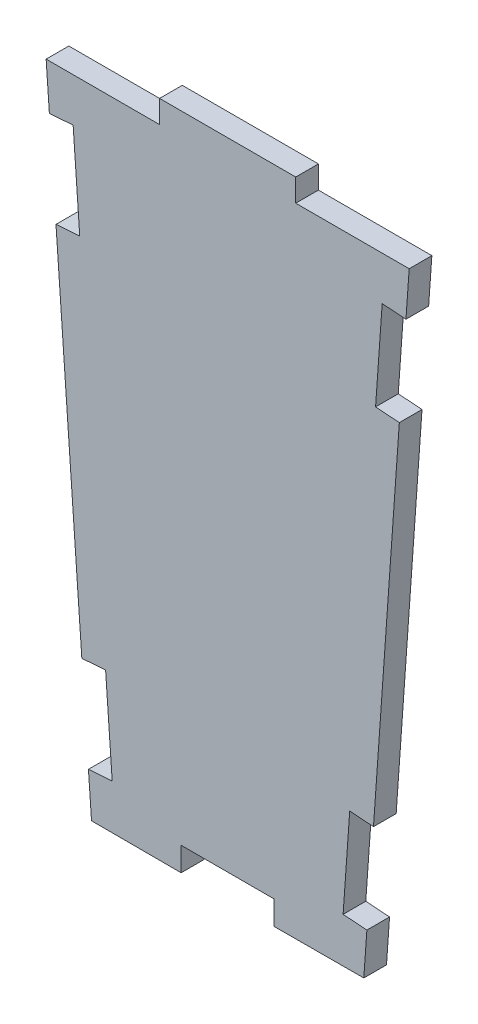
SolidWorks part; units mm, degrees
ref_plane "Front Plane" through (0, 0, 0) normal (0, 0, 1) x (1, 0, 0)
ref_plane "Top Plane" through (0, 0, 0) normal (0, 1, 0) x (1, 0, 0)
ref_plane "Right Plane" through (0, 0, 0) normal (1, 0, 0) x (0, 0, -1)
sketch "Model" plane through (0, 0, 0) normal (0, 0, 1) x (1, 0, 0)
  line L0 (354.4597, -23.3264) -> (359.6964, -22.9533)
  line L1 (383.497, -148.4797) -> (403.9964, -148.4797)
  line L2 (425.8801, -123.7434) -> (420.6434, -123.3703)
  line L3 (353.747, -13.3232) -> (354.4597, -23.3264)
  line L4 (383.4969, -153.7291) -> (383.497, -148.4797)
  line L5 (420.6434, -123.3703) -> (419.1865, -143.8185)
  line L6 (366.8507, -123.3703) -> (368.3075, -143.8185)
  line L7 (426.3408, -43.4015) -> (431.5775, -43.7746)
  line L8 (378.747, -8.3232) -> (408.747, -8.3232)
  line L9 (363.0708, -144.1916) -> (363.747, -153.6832)
  line L10 (419.1865, -143.8185) -> (424.4233, -144.1916)
  line L11 (408.747, -8.3232) -> (408.747, -13.3232)
  line L12 (423.747, -153.6832) -> (403.9971, -153.7291)
  line L13 (403.9964, -148.4797) -> (403.9971, -153.7291)
  line L14 (378.747, -8.3232) -> (378.747, -13.3232)
  line L15 (361.6139, -123.7434) -> (366.8507, -123.3703)
  line L16 (433.747, -13.3232) -> (433.0343, -23.3264)
  line L17 (361.1533, -43.4015) -> (355.9165, -43.7746)
  line L18 (431.5775, -43.7746) -> (425.8801, -123.7434)
  line L19 (359.6964, -22.9533) -> (361.1533, -43.4015)
  line L20 (427.7976, -22.9533) -> (426.3408, -43.4015)
  line L21 (355.9165, -43.7746) -> (361.6139, -123.7434)
  line L22 (408.747, -13.3232) -> (433.747, -13.3232)
  line L23 (368.3075, -143.8185) -> (363.0708, -144.1916)
  line L24 (378.747, -13.3232) -> (353.747, -13.3232)
  line L25 (433.0343, -23.3264) -> (427.7976, -22.9533)
  line L26 (363.747, -153.6832) -> (383.4969, -153.7291)
  line L27 (424.4233, -144.1916) -> (423.747, -153.6832)
  line L28 (393.747, -16.3232) -> (393.747, -11.3232)
  line L29 (394.747, -13.3232) -> (393.747, -11.3232)
  line L30 (392.747, -13.3232) -> (393.747, -11.3232)
  line L31 (395.617, -18.1099) -> (395.617, -17.804)
  line L32 (395.617, -17.804) -> (395.6373, -17.7076)
  line L33 (395.6373, -17.7076) -> (395.6982, -17.6183)
  line L34 (395.6982, -17.6183) -> (395.9417, -17.4606)
  line L35 (395.9417, -17.4606) -> (396.2976, -17.3576)
  line L36 (396.2976, -17.3576) -> (396.7409, -17.3232)
  line L37 (396.7409, -17.3232) -> (397.1858, -17.3576)
  line L38 (397.1858, -17.3576) -> (397.5464, -17.4606)
  line L39 (397.5464, -17.4606) -> (397.7852, -17.6151)
  line L40 (397.7852, -17.6151) -> (397.8449, -17.7053)
  line L41 (397.8449, -17.7053) -> (397.8648, -17.804)
  line L42 (397.8648, -17.804) -> (397.8648, -21.1504)
  line L43 (397.8648, -21.1504) -> (397.8449, -21.2464)
  line L44 (397.8449, -21.2464) -> (397.7852, -21.3346)
  line L45 (397.7852, -21.3346) -> (397.5464, -21.4876)
  line L46 (397.5464, -21.4876) -> (397.1796, -21.5953)
  line L47 (397.1796, -21.5953) -> (396.7409, -21.6312)
  line L48 (396.7409, -21.6312) -> (396.307, -21.5953)
  line L49 (396.307, -21.5953) -> (395.9417, -21.4876)
  line L50 (395.9417, -21.4876) -> (395.6982, -21.3315)
  line L51 (395.6982, -21.3315) -> (395.6373, -21.2441)
  line L52 (395.6373, -21.2441) -> (395.617, -21.1504)
  line L53 (395.617, -21.1504) -> (395.617, -20.8445)
  line L54 (395.617, -20.8445) -> (395.617, -21.1504)
  line L55 (395.617, -21.1504) -> (395.6373, -21.2441)
  line L56 (395.6373, -21.2441) -> (395.6982, -21.3315)
  line L57 (395.6982, -21.3315) -> (395.9417, -21.4876)
  line L58 (395.9417, -21.4876) -> (396.307, -21.5953)
  line L59 (396.307, -21.5953) -> (396.7409, -21.6312)
  line L60 (396.7409, -21.6312) -> (397.1796, -21.5953)
  line L61 (397.1796, -21.5953) -> (397.5464, -21.4876)
  line L62 (397.5464, -21.4876) -> (397.7852, -21.3346)
  line L63 (397.7852, -21.3346) -> (397.8449, -21.2464)
  line L64 (397.8449, -21.2464) -> (397.8648, -21.1504)
  line L65 (397.8648, -21.1504) -> (397.8648, -17.804)
  line L66 (397.8648, -17.804) -> (397.8449, -17.7053)
  line L67 (397.8449, -17.7053) -> (397.7852, -17.6151)
  line L68 (397.7852, -17.6151) -> (397.5464, -17.4606)
  line L69 (397.5464, -17.4606) -> (397.1858, -17.3576)
  line L70 (397.1858, -17.3576) -> (396.7409, -17.3232)
  line L71 (396.7409, -17.3232) -> (396.2976, -17.3576)
  line L72 (396.2976, -17.3576) -> (395.9417, -17.4606)
  line L73 (395.9417, -17.4606) -> (395.6982, -17.6183)
  line L74 (395.6982, -17.6183) -> (395.6373, -17.7076)
  line L75 (395.6373, -17.7076) -> (395.617, -17.804)
  line L76 (395.617, -17.804) -> (395.617, -18.1099)
  line L77 (394.874, -17.3232) -> (394.874, -21.6312)
  line L78 (394.874, -21.6312) -> (393.8562, -21.6312)
  line L79 (393.8562, -21.6312) -> (393.4223, -21.5953)
  line L80 (393.4223, -21.5953) -> (393.057, -21.4876)
  line L81 (393.057, -21.4876) -> (392.8135, -21.3315)
  line L82 (392.8135, -21.3315) -> (392.7526, -21.2441)
  line L83 (392.7526, -21.2441) -> (392.7323, -21.1504)
  line L84 (392.7323, -21.1504) -> (392.7323, -17.804)
  line L85 (392.7323, -17.804) -> (392.7526, -17.7076)
  line L86 (392.7526, -17.7076) -> (392.8135, -17.6183)
  line L87 (392.8135, -17.6183) -> (393.057, -17.4606)
  line L88 (393.057, -17.4606) -> (393.4129, -17.3576)
  line L89 (393.4129, -17.3576) -> (393.8562, -17.3232)
  line L90 (393.8562, -17.3232) -> (394.874, -17.3232)
  line L91 (394.874, -21.6312) -> (394.874, -17.3232)
  line L92 (394.874, -17.3232) -> (393.8562, -17.3232)
  line L93 (393.8562, -17.3232) -> (393.4129, -17.3576)
  line L94 (393.4129, -17.3576) -> (393.057, -17.4606)
  line L95 (393.057, -17.4606) -> (392.8135, -17.6183)
  line L96 (392.8135, -17.6183) -> (392.7526, -17.7076)
  line L97 (392.7526, -17.7076) -> (392.7323, -17.804)
  line L98 (392.7323, -17.804) -> (392.7323, -21.1504)
  line L99 (392.7323, -21.1504) -> (392.7526, -21.2441)
  line L100 (392.7526, -21.2441) -> (392.8135, -21.3315)
  line L101 (392.8135, -21.3315) -> (393.057, -21.4876)
  line L102 (393.057, -21.4876) -> (393.4223, -21.5953)
  line L103 (393.4223, -21.5953) -> (393.8562, -21.6312)
  line L104 (393.8562, -21.6312) -> (394.874, -21.6312)
  line L105 (390.7531, -17.3232) -> (391.1941, -17.3584)
  line L106 (391.1941, -17.3584) -> (391.5555, -17.4637)
  line L107 (391.5555, -17.4637) -> (391.7966, -17.619)
  line L108 (391.7966, -17.619) -> (391.8569, -17.7078)
  line L109 (391.8569, -17.7078) -> (391.877, -17.804)
  line L110 (391.877, -17.804) -> (391.8569, -17.7078)
  line L111 (391.8569, -17.7078) -> (391.7966, -17.619)
  line L112 (391.7966, -17.619) -> (391.5555, -17.4637)
  line L113 (389.9508, -17.4637) -> (389.7096, -17.619)
  line L114 (389.7096, -17.619) -> (389.6493, -17.7078)
  line L115 (389.6493, -17.7078) -> (389.6292, -17.804)
  line L116 (389.6292, -17.804) -> (389.6292, -19.5147)
  line L117 (389.6292, -19.5147) -> (389.6493, -19.6109)
  line L118 (389.6493, -19.6109) -> (389.7096, -19.6997)
  line L119 (389.7096, -19.6997) -> (389.9508, -19.855)
  line L120 (389.9508, -19.855) -> (390.3121, -19.9603)
  line L121 (390.3121, -19.9603) -> (390.7531, -19.9955)
  line L122 (390.7531, -19.9955) -> (391.4275, -19.8955)
  line L123 (391.4275, -19.8955) -> (391.6585, -19.7691)
  line L124 (391.6585, -19.7691) -> (391.877, -19.5147)
  line L125 (391.877, -19.5147) -> (391.877, -21.6312)
  line L126 (391.877, -21.6312) -> (389.7042, -21.6312)
  line L127 (389.7042, -21.6312) -> (391.877, -21.6312)
  line L128 (391.877, -21.6312) -> (391.877, -19.5147)
  line L129 (391.877, -19.5147) -> (391.6585, -19.7691)
  line L130 (391.6585, -19.7691) -> (391.4275, -19.8955)
  line L131 (391.4275, -19.8955) -> (390.7531, -19.9955)
  line L132 (390.7531, -19.9955) -> (390.3121, -19.9603)
  line L133 (390.3121, -19.9603) -> (389.9508, -19.855)
  line L134 (389.9508, -19.855) -> (389.7096, -19.6997)
  line L135 (389.7096, -19.6997) -> (389.6493, -19.6109)
  line L136 (389.6493, -19.6109) -> (389.6292, -19.5147)
  line L137 (389.6292, -19.5147) -> (389.6292, -17.804)
  line L138 (389.6292, -17.804) -> (389.6493, -17.7078)
  line L139 (389.6493, -17.7078) -> (389.7096, -17.619)
  line L140 (389.7096, -17.619) -> (389.9508, -17.4637)
  line L141 (389.9508, -17.4637) -> (390.3121, -17.3584)
  line L142 (390.3121, -17.3584) -> (390.7531, -17.3232)
  line L143 (383.3916, -131.5778) -> (383.1481, -131.7354)
  line L144 (384.9963, -135.6048) -> (385.2351, -135.4518)
  line L145 (381.1999, -135.7484) -> (380.759, -135.7132)
  line L146 (385.3147, -135.2676) -> (385.3147, -131.9212)
  line L147 (385.2351, -135.4518) -> (385.2948, -135.3636)
  line L148 (383.0872, -135.3613) -> (383.1481, -135.4487)
  line L149 (384.1908, -135.7484) -> (383.7569, -135.7125)
  line L150 (383.1481, -131.7354) -> (383.0872, -131.8248)
  line L151 (383.0669, -131.9212) -> (383.0669, -132.2271)
  line L152 (380.076, -131.9212) -> (380.0961, -131.825)
  line L153 (383.7569, -135.7125) -> (383.3916, -135.6048)
  line L154 (385.3147, -131.9212) -> (385.2948, -131.8225)
  line L155 (384.9963, -131.5778) -> (384.6357, -131.4748)
  line L156 (382.2435, -135.4526) -> (382.0023, -135.6079)
  line L157 (383.0872, -135.3613) -> (383.0669, -135.2676)
  line L158 (381.6409, -135.7132) -> (381.1999, -135.7484)
  line L159 (380.759, -135.7132) -> (380.3976, -135.6079)
  line L160 (380.076, -134.9617) -> (380.076, -135.2676)
  line L161 (384.1908, -135.7484) -> (384.6294, -135.7125)
  line L162 (381.6409, -135.7132) -> (382.0023, -135.6079)
  line L163 (382.2435, -135.4526) -> (382.3038, -135.3638)
  line L164 (382.3038, -135.3638) -> (382.3239, -135.2676)
  line L165 (382.3239, -135.2676) -> (382.3239, -131.9212)
  line L166 (380.076, -135.2676) -> (380.0961, -135.3638)
  line L167 (383.0669, -135.2676) -> (383.0669, -134.9617)
  line L168 (384.1908, -131.4404) -> (383.7475, -131.4748)
  line L169 (385.2948, -135.3636) -> (385.3147, -135.2676)
  line L170 (383.7475, -131.4748) -> (383.3916, -131.5778)
  line L171 (383.0872, -131.8248) -> (383.0669, -131.9212)
  line L172 (383.1481, -135.4487) -> (383.3916, -135.6048)
  line L173 (380.1564, -135.4526) -> (380.0961, -135.3638)
  line L174 (384.6357, -131.4748) -> (384.1908, -131.4404)
  line L175 (384.6294, -135.7125) -> (384.9963, -135.6048)
  line L176 (385.2948, -131.8225) -> (385.2351, -131.7323)
  line L177 (385.2351, -131.7323) -> (384.9963, -131.5778)
  line L178 (380.1564, -135.4526) -> (380.3976, -135.6079)
  line L179 (380.1564, -131.7362) -> (380.0961, -131.825)
  line L180 (377.762, -131.4756) -> (378.203, -131.4404)
  line L181 (377.4006, -131.5809) -> (377.762, -131.4756)
  line L182 (380.759, -131.4756) -> (380.3976, -131.5809)
  line L183 (378.203, -131.4404) -> (378.644, -131.4756)
  line L184 (379.2465, -131.7362) -> (379.0054, -131.5809)
  line L185 (382.2435, -131.7362) -> (382.0023, -131.5809)
  line L186 (382.3038, -131.825) -> (382.2435, -131.7362)
  line L187 (379.1084, -133.8863) -> (378.8774, -134.0127)
  line L188 (378.203, -134.1126) -> (377.762, -134.0775)
  line L189 (379.3068, -131.825) -> (379.2465, -131.7362)
  line L190 (377.4006, -133.9722) -> (377.1595, -133.8168)
  line L191 (380.3976, -131.5809) -> (380.1564, -131.7362)
  line L192 (377.1595, -133.8168) -> (377.0992, -133.728)
  line L193 (379.3269, -131.9212) -> (379.3068, -131.825)
  line L194 (377.0791, -131.9212) -> (377.0992, -131.825)
  line L195 (382.0023, -131.5809) -> (381.6409, -131.4756)
  line L196 (380.076, -133.5944) -> (380.076, -131.9212)
  line L197 (377.4006, -131.5809) -> (377.1595, -131.7362)
  line L198 (377.154, -135.7484) -> (379.3269, -135.7484)
  line L199 (378.8774, -134.0127) -> (378.203, -134.1126)
  line L200 (377.0992, -131.825) -> (377.1595, -131.7362)
  line L201 (381.6409, -131.4756) -> (381.1999, -131.4404)
  line L202 (377.0791, -131.9212) -> (377.0791, -133.6318)
  line L203 (381.1875, -133.5944) -> (380.076, -133.5944)
  line L204 (379.3269, -135.7484) -> (379.3269, -133.6318)
  line L205 (377.4006, -133.9722) -> (377.762, -134.0775)
  line L206 (377.0992, -133.728) -> (377.0791, -133.6318)
  line L207 (381.1999, -131.4404) -> (380.759, -131.4756)
  line L208 (378.644, -131.4756) -> (379.0054, -131.5809)
  line L209 (379.3269, -133.6318) -> (379.1084, -133.8863)
  line L210 (382.3239, -131.9212) -> (382.3038, -131.825)
  line L211 (374.5791, -133.5944) -> (369.5791, -133.5944)
  line L212 (371.5791, -132.5944) -> (369.5791, -133.5944)
  line L213 (371.5791, -134.5944) -> (369.5791, -133.5944)
  line L214 (415.6461, -31.1608) -> (415.4026, -31.3185)
  line L215 (417.2507, -35.1878) -> (417.4896, -35.0348)
  line L216 (413.4544, -35.3314) -> (413.0135, -35.2963)
  line L217 (417.5692, -34.8506) -> (417.5692, -31.5042)
  line L218 (417.4896, -35.0348) -> (417.5493, -34.9466)
  line L219 (415.3417, -34.9443) -> (415.4026, -35.0317)
  line L220 (416.4453, -35.3314) -> (416.0114, -35.2955)
  line L221 (415.4026, -31.3185) -> (415.3417, -31.4078)
  line L222 (415.3214, -31.5042) -> (415.3214, -31.8101)
  line L223 (412.3305, -31.5042) -> (412.3506, -31.408)
  line L224 (416.0114, -35.2955) -> (415.6461, -35.1878)
  line L225 (417.5692, -31.5042) -> (417.5493, -31.4055)
  line L226 (417.2507, -31.1608) -> (416.8902, -31.0578)
  line L227 (414.498, -35.0356) -> (414.2568, -35.1909)
  line L228 (415.3417, -34.9443) -> (415.3214, -34.8506)
  line L229 (413.8954, -35.2963) -> (413.4544, -35.3314)
  line L230 (413.0135, -35.2963) -> (412.6521, -35.1909)
  line L231 (412.3305, -34.5447) -> (412.3305, -34.8506)
  line L232 (416.4453, -35.3314) -> (416.8839, -35.2955)
  line L233 (413.8954, -35.2963) -> (414.2568, -35.1909)
  line L234 (414.498, -35.0356) -> (414.5582, -34.9468)
  line L235 (414.5582, -34.9468) -> (414.5783, -34.8506)
  line L236 (414.5783, -34.8506) -> (414.5783, -31.5042)
  line L237 (412.3305, -34.8506) -> (412.3506, -34.9468)
  line L238 (415.3214, -34.8506) -> (415.3214, -34.5447)
  line L239 (416.4453, -31.0235) -> (416.002, -31.0578)
  line L240 (417.5493, -34.9466) -> (417.5692, -34.8506)
  line L241 (416.002, -31.0578) -> (415.6461, -31.1608)
  line L242 (415.3417, -31.4078) -> (415.3214, -31.5042)
  line L243 (415.4026, -35.0317) -> (415.6461, -35.1878)
  line L244 (412.4109, -35.0356) -> (412.3506, -34.9468)
  line L245 (416.8902, -31.0578) -> (416.4453, -31.0235)
  line L246 (416.8839, -35.2955) -> (417.2507, -35.1878)
  line L247 (417.5493, -31.4055) -> (417.4896, -31.3153)
  line L248 (417.4896, -31.3153) -> (417.2507, -31.1608)
  line L249 (412.4109, -35.0356) -> (412.6521, -35.1909)
  line L250 (412.4109, -31.3192) -> (412.3506, -31.408)
  line L251 (410.0165, -31.0586) -> (410.4575, -31.0235)
  line L252 (409.6551, -31.1639) -> (410.0165, -31.0586)
  line L253 (413.0135, -31.0586) -> (412.6521, -31.1639)
  line L254 (410.4575, -31.0235) -> (410.8985, -31.0586)
  line L255 (411.501, -31.3192) -> (411.2598, -31.1639)
  line L256 (414.498, -31.3192) -> (414.2568, -31.1639)
  line L257 (414.5582, -31.408) -> (414.498, -31.3192)
  line L258 (411.3629, -33.4693) -> (411.1318, -33.5957)
  line L259 (410.4575, -33.6957) -> (410.0165, -33.6605)
  line L260 (411.5613, -31.408) -> (411.501, -31.3192)
  line L261 (409.6551, -33.5552) -> (409.414, -33.3999)
  line L262 (412.6521, -31.1639) -> (412.4109, -31.3192)
  line L263 (409.414, -33.3999) -> (409.3537, -33.3111)
  line L264 (411.5814, -31.5042) -> (411.5613, -31.408)
  line L265 (409.3336, -31.5042) -> (409.3537, -31.408)
  line L266 (414.2568, -31.1639) -> (413.8954, -31.0586)
  line L267 (412.3305, -33.1774) -> (412.3305, -31.5042)
  line L268 (409.6551, -31.1639) -> (409.414, -31.3192)
  line L269 (409.4085, -35.3314) -> (411.5814, -35.3314)
  line L270 (411.1318, -33.5957) -> (410.4575, -33.6957)
  line L271 (409.3537, -31.408) -> (409.414, -31.3192)
  line L272 (413.8954, -31.0586) -> (413.4544, -31.0235)
  line L273 (409.3336, -31.5042) -> (409.3336, -33.2149)
  line L274 (413.442, -33.1774) -> (412.3305, -33.1774)
  line L275 (411.5814, -35.3314) -> (411.5814, -33.2149)
  line L276 (409.6551, -33.5552) -> (410.0165, -33.6605)
  line L277 (409.3537, -33.3111) -> (409.3336, -33.2149)
  line L278 (413.4544, -31.0235) -> (413.0135, -31.0586)
  line L279 (410.8985, -31.0586) -> (411.2598, -31.1639)
  line L280 (411.5814, -33.2149) -> (411.3629, -33.4693)
  line L281 (414.5783, -31.5042) -> (414.5582, -31.408)
  line L282 (420.0692, -33.1774) -> (425.0692, -33.1774)
  line L283 (423.0692, -34.1774) -> (425.0692, -33.1774)
  line L284 (423.0692, -32.1774) -> (425.0692, -33.1774)
  line L285 (408.4918, -131.5778) -> (408.2483, -131.7354)
  line L286 (410.0965, -135.6048) -> (410.3353, -135.4518)
  line L287 (406.3002, -135.7484) -> (405.8592, -135.7132)
  line L288 (410.415, -135.2676) -> (410.415, -131.9212)
  line L289 (410.3353, -135.4518) -> (410.3951, -135.3636)
  line L290 (408.1874, -135.3613) -> (408.2483, -135.4487)
  line L291 (409.2911, -135.7484) -> (408.8571, -135.7125)
  line L292 (408.2483, -131.7354) -> (408.1874, -131.8248)
  line L293 (408.1671, -131.9212) -> (408.1671, -132.2271)
  line L294 (405.1763, -131.9212) -> (405.1964, -131.825)
  line L295 (408.8571, -135.7125) -> (408.4918, -135.6048)
  line L296 (410.415, -131.9212) -> (410.3951, -131.8225)
  line L297 (410.0965, -131.5778) -> (409.7359, -131.4748)
  line L298 (407.3437, -135.4526) -> (407.1025, -135.6079)
  line L299 (408.1874, -135.3613) -> (408.1671, -135.2676)
  line L300 (406.7412, -135.7132) -> (406.3002, -135.7484)
  line L301 (405.8592, -135.7132) -> (405.4978, -135.6079)
  line L302 (405.1763, -134.9617) -> (405.1763, -135.2676)
  line L303 (409.2911, -135.7484) -> (409.7297, -135.7125)
  line L304 (406.7412, -135.7132) -> (407.1025, -135.6079)
  line L305 (407.3437, -135.4526) -> (407.404, -135.3638)
  line L306 (407.404, -135.3638) -> (407.4241, -135.2676)
  line L307 (407.4241, -135.2676) -> (407.4241, -131.9212)
  line L308 (405.1763, -135.2676) -> (405.1964, -135.3638)
  line L309 (408.1671, -135.2676) -> (408.1671, -134.9617)
  line L310 (409.2911, -131.4404) -> (408.8477, -131.4748)
  line L311 (410.3951, -135.3636) -> (410.415, -135.2676)
  line L312 (408.8477, -131.4748) -> (408.4918, -131.5778)
  line L313 (408.1874, -131.8248) -> (408.1671, -131.9212)
  line L314 (408.2483, -135.4487) -> (408.4918, -135.6048)
  line L315 (405.2567, -135.4526) -> (405.1964, -135.3638)
  line L316 (409.7359, -131.4748) -> (409.2911, -131.4404)
  line L317 (409.7297, -135.7125) -> (410.0965, -135.6048)
  line L318 (410.3951, -131.8225) -> (410.3353, -131.7323)
  line L319 (410.3353, -131.7323) -> (410.0965, -131.5778)
  line L320 (405.2567, -135.4526) -> (405.4978, -135.6079)
  line L321 (405.2567, -131.7362) -> (405.1964, -131.825)
  line L322 (402.8623, -131.4756) -> (403.3032, -131.4404)
  line L323 (402.5009, -131.5809) -> (402.8623, -131.4756)
  line L324 (405.8592, -131.4756) -> (405.4978, -131.5809)
  line L325 (403.3032, -131.4404) -> (403.7442, -131.4756)
  line L326 (404.3468, -131.7362) -> (404.1056, -131.5809)
  line L327 (407.3437, -131.7362) -> (407.1025, -131.5809)
  line L328 (407.404, -131.825) -> (407.3437, -131.7362)
  line L329 (404.2086, -133.8863) -> (403.9776, -134.0127)
  line L330 (403.3032, -134.1126) -> (402.8623, -134.0775)
  line L331 (404.4071, -131.825) -> (404.3468, -131.7362)
  line L332 (402.5009, -133.9722) -> (402.2597, -133.8168)
  line L333 (405.4978, -131.5809) -> (405.2567, -131.7362)
  line L334 (402.2597, -133.8168) -> (402.1994, -133.728)
  line L335 (404.4271, -131.9212) -> (404.4071, -131.825)
  line L336 (402.1793, -131.9212) -> (402.1994, -131.825)
  line L337 (407.1025, -131.5809) -> (406.7412, -131.4756)
  line L338 (405.1763, -133.5944) -> (405.1763, -131.9212)
  line L339 (402.5009, -131.5809) -> (402.2597, -131.7362)
  line L340 (402.2543, -135.7484) -> (404.4271, -135.7484)
  line L341 (403.9776, -134.0127) -> (403.3032, -134.1126)
  line L342 (402.1994, -131.825) -> (402.2597, -131.7362)
  line L343 (406.7412, -131.4756) -> (406.3002, -131.4404)
  line L344 (402.1793, -131.9212) -> (402.1793, -133.6318)
  line L345 (406.2877, -133.5944) -> (405.1763, -133.5944)
  line L346 (404.4271, -135.7484) -> (404.4271, -133.6318)
  line L347 (402.5009, -133.9722) -> (402.8623, -134.0775)
  line L348 (402.1994, -133.728) -> (402.1793, -133.6318)
  line L349 (406.3002, -131.4404) -> (405.8592, -131.4756)
  line L350 (403.7442, -131.4756) -> (404.1056, -131.5809)
  line L351 (404.4271, -133.6318) -> (404.2086, -133.8863)
  line L352 (407.4241, -131.9212) -> (407.404, -131.825)
  line L353 (412.915, -133.5944) -> (417.915, -133.5944)
  line L354 (415.915, -134.5944) -> (417.915, -133.5944)
  line L355 (415.915, -132.5944) -> (417.915, -133.5944)
  line L356 (376.2373, -31.1608) -> (375.9938, -31.3185)
  line L357 (377.842, -35.1878) -> (378.0808, -35.0348)
  line L358 (374.0457, -35.3314) -> (373.6047, -35.2963)
  line L359 (378.1605, -34.8506) -> (378.1605, -31.5042)
  line L360 (378.0808, -35.0348) -> (378.1406, -34.9466)
  line L361 (375.9329, -34.9443) -> (375.9938, -35.0317)
  line L362 (377.0366, -35.3314) -> (376.6026, -35.2955)
  line L363 (375.9938, -31.3185) -> (375.9329, -31.4078)
  line L364 (375.9127, -31.5042) -> (375.9127, -31.8101)
  line L365 (372.9218, -31.5042) -> (372.9419, -31.408)
  line L366 (376.6026, -35.2955) -> (376.2373, -35.1878)
  line L367 (378.1605, -31.5042) -> (378.1406, -31.4055)
  line L368 (377.842, -31.1608) -> (377.4814, -31.0578)
  line L369 (375.0892, -35.0356) -> (374.8481, -35.1909)
  line L370 (375.9329, -34.9443) -> (375.9127, -34.8506)
  line L371 (374.4867, -35.2963) -> (374.0457, -35.3314)
  line L372 (373.6047, -35.2963) -> (373.2434, -35.1909)
  line L373 (372.9218, -34.5447) -> (372.9218, -34.8506)
  line L374 (377.0366, -35.3314) -> (377.4752, -35.2955)
  line L375 (374.4867, -35.2963) -> (374.8481, -35.1909)
  line L376 (375.0892, -35.0356) -> (375.1495, -34.9468)
  line L377 (375.1495, -34.9468) -> (375.1696, -34.8506)
  line L378 (375.1696, -34.8506) -> (375.1696, -31.5042)
  line L379 (372.9218, -34.8506) -> (372.9419, -34.9468)
  line L380 (375.9127, -34.8506) -> (375.9127, -34.5447)
  line L381 (377.0366, -31.0235) -> (376.5932, -31.0578)
  line L382 (378.1406, -34.9466) -> (378.1605, -34.8506)
  line L383 (376.5932, -31.0578) -> (376.2373, -31.1608)
  line L384 (375.9329, -31.4078) -> (375.9127, -31.5042)
  line L385 (375.9938, -35.0317) -> (376.2373, -35.1878)
  line L386 (373.0022, -35.0356) -> (372.9419, -34.9468)
  line L387 (377.4814, -31.0578) -> (377.0366, -31.0235)
  line L388 (377.4752, -35.2955) -> (377.842, -35.1878)
  line L389 (378.1406, -31.4055) -> (378.0808, -31.3153)
  line L390 (378.0808, -31.3153) -> (377.842, -31.1608)
  line L391 (373.0022, -35.0356) -> (373.2434, -35.1909)
  line L392 (373.0022, -31.3192) -> (372.9419, -31.408)
  line L393 (370.6078, -31.0586) -> (371.0488, -31.0235)
  line L394 (370.2464, -31.1639) -> (370.6078, -31.0586)
  line L395 (373.6047, -31.0586) -> (373.2434, -31.1639)
  line L396 (371.0488, -31.0235) -> (371.4897, -31.0586)
  line L397 (372.0923, -31.3192) -> (371.8511, -31.1639)
  line L398 (375.0892, -31.3192) -> (374.8481, -31.1639)
  line L399 (375.1495, -31.408) -> (375.0892, -31.3192)
  line L400 (371.9541, -33.4693) -> (371.7231, -33.5957)
  line L401 (371.0488, -33.6957) -> (370.6078, -33.6605)
  line L402 (372.1526, -31.408) -> (372.0923, -31.3192)
  line L403 (370.2464, -33.5552) -> (370.0052, -33.3999)
  line L404 (373.2434, -31.1639) -> (373.0022, -31.3192)
  line L405 (370.0052, -33.3999) -> (369.9449, -33.3111)
  line L406 (372.1727, -31.5042) -> (372.1526, -31.408)
  line L407 (369.9248, -31.5042) -> (369.9449, -31.408)
  line L408 (374.8481, -31.1639) -> (374.4867, -31.0586)
  line L409 (372.9218, -33.1774) -> (372.9218, -31.5042)
  line L410 (370.2464, -31.1639) -> (370.0052, -31.3192)
  line L411 (369.9998, -35.3314) -> (372.1727, -35.3314)
  line L412 (371.7231, -33.5957) -> (371.0488, -33.6957)
  line L413 (369.9449, -31.408) -> (370.0052, -31.3192)
  line L414 (374.4867, -31.0586) -> (374.0457, -31.0235)
  line L415 (369.9248, -31.5042) -> (369.9248, -33.2149)
  line L416 (374.0332, -33.1774) -> (372.9218, -33.1774)
  line L417 (372.1727, -35.3314) -> (372.1727, -33.2149)
  line L418 (370.2464, -33.5552) -> (370.6078, -33.6605)
  line L419 (369.9449, -33.3111) -> (369.9248, -33.2149)
  line L420 (374.0457, -31.0235) -> (373.6047, -31.0586)
  line L421 (371.4897, -31.0586) -> (371.8511, -31.1639)
  line L422 (372.1727, -33.2149) -> (371.9541, -33.4693)
  line L423 (375.1696, -31.5042) -> (375.1495, -31.408)
  line L424 (367.4248, -33.1774) -> (362.4248, -33.1774)
  line L425 (364.4248, -32.1774) -> (362.4248, -33.1774)
  line L426 (364.4248, -34.1774) -> (362.4248, -33.1774)
  line L427 (393.7467, -141.4797) -> (393.7467, -146.4797)
  line L428 (392.7467, -144.4797) -> (393.7467, -146.4797)
  line L429 (394.7467, -144.4797) -> (393.7467, -146.4797)
  line L430 (395.9414, -140.3361) -> (396.3067, -140.4438)
  line L431 (397.5461, -136.3091) -> (397.1855, -136.2061)
  line L432 (395.6167, -139.9989) -> (395.637, -140.0926)
  line L433 (396.7406, -140.4797) -> (397.1793, -140.4438)
  line L434 (397.8645, -139.9989) -> (397.8645, -136.6525)
  line L435 (391.8566, -136.5563) -> (391.7963, -136.4675)
  line L436 (389.7039, -140.4797) -> (391.8767, -140.4797)
  line L437 (397.7849, -136.4636) -> (397.5461, -136.3091)
  line L438 (392.6384, -140.4797) -> (392.6384, -138.3571)
  line L439 (391.4272, -138.744) -> (390.7528, -138.8439)
  line L440 (397.8446, -140.0949) -> (397.8645, -139.9989)
  line L441 (391.8767, -138.3631) -> (391.6582, -138.6176)
  line L442 (391.8767, -138.3631) -> (391.8767, -140.4797)
  line L443 (389.7093, -138.5481) -> (389.9505, -138.7035)
  line L444 (391.6582, -138.6176) -> (391.4272, -138.744)
  line L445 (395.637, -140.0926) -> (395.6979, -140.18)
  line L446 (397.8645, -136.6525) -> (397.8446, -136.5538)
  line L447 (395.9414, -136.3091) -> (395.6979, -136.4667)
  line L448 (390.7528, -138.8439) -> (390.3118, -138.8088)
  line L449 (396.3067, -140.4438) -> (396.7406, -140.4797)
  line L450 (390.3118, -138.8088) -> (389.9505, -138.7035)
  line L451 (389.7093, -138.5481) -> (389.649, -138.4594)
  line L452 (389.6289, -138.3631) -> (389.6289, -136.6525)
  line L453 (389.649, -138.4594) -> (389.6289, -138.3631)
  line L454 (395.6979, -140.18) -> (395.9414, -140.3361)
  line L455 (397.1855, -136.2061) -> (396.7406, -136.1717)
  line L456 (395.6167, -136.6525) -> (395.6167, -136.9584)
  line L457 (394.8737, -138.3571) -> (392.6384, -138.3571)
  line L458 (394.8737, -138.3571) -> (394.8737, -140.4797)
  line L459 (397.5461, -140.3361) -> (397.7849, -140.1831)
  line L460 (395.6167, -139.693) -> (395.6167, -139.9989)
  line L461 (394.8737, -136.1717) -> (394.8737, -138.3571)
  line L462 (396.2973, -136.2061) -> (395.9414, -136.3091)
  line L463 (397.1793, -140.4438) -> (397.5461, -140.3361)
  line L464 (397.7849, -140.1831) -> (397.8446, -140.0949)
  line L465 (391.1938, -136.2069) -> (391.5552, -136.3122)
  line L466 (395.637, -136.5561) -> (395.6167, -136.6525)
  line L467 (391.7963, -136.4675) -> (391.5552, -136.3122)
  line L468 (395.6979, -136.4667) -> (395.637, -136.5561)
  line L469 (396.7406, -136.1717) -> (396.2973, -136.2061)
  line L470 (391.8767, -136.6525) -> (391.8566, -136.5563)
  line L471 (397.8446, -136.5538) -> (397.7849, -136.4636)
  line L472 (390.7528, -136.1717) -> (391.1938, -136.2069)
  line L473 (389.7093, -136.4675) -> (389.9505, -136.3122)
  line L474 (390.3118, -136.2069) -> (390.7528, -136.1717)
  line L475 (389.649, -136.5563) -> (389.7093, -136.4675)
  line L476 (389.9505, -136.3122) -> (390.3118, -136.2069)
  line L477 (392.6384, -138.3571) -> (392.6384, -136.1717)
  line L478 (389.6289, -136.6525) -> (389.649, -136.5563)
  line L479 (401.9074, -73.4797) -> (385.5861, -73.4797)
  line L480 (400.1935, -72.4766) -> (400.7336, -72.4766)
  line L481 (400.7336, -72.4766) -> (399.6628, -72.4766)
  line L482 (399.6628, -72.4766) -> (400.1935, -72.4766)
  line L483 (400.1935, -72.4766) -> (400.1935, -70.3227)
  line L484 (400.1935, -70.3227) -> (400.1935, -72.4766)
  line L485 (399.2352, -70.3227) -> (399.2352, -72.4766)
  line L486 (399.2352, -72.4766) -> (399.2352, -71.4151)
  line L487 (399.2352, -71.4151) -> (398.1175, -71.4151)
  line L488 (398.1175, -71.4151) -> (398.1175, -72.4766)
  line L489 (398.1175, -72.4766) -> (398.1175, -70.3227)
  line L490 (398.1175, -70.3227) -> (398.1175, -71.4153)
  line L491 (398.1175, -71.4153) -> (399.2352, -71.4153)
  line L492 (399.2352, -71.4153) -> (399.2352, -70.3227)
  line L493 (397.7367, -72.4797) -> (397.7367, -70.3227)
  line L494 (397.2367, -70.716) -> (397.2367, -70.563)
  line L495 (397.2367, -70.563) -> (397.2266, -70.5149)
  line L496 (397.2266, -70.5149) -> (397.1965, -70.4706)
  line L497 (397.1965, -70.4706) -> (397.0759, -70.3929)
  line L498 (397.0759, -70.3929) -> (396.8952, -70.3402)
  line L499 (396.8952, -70.3402) -> (396.6747, -70.3227)
  line L500 (396.6747, -70.3227) -> (396.4542, -70.3402)
  line L501 (396.4542, -70.3402) -> (396.2736, -70.3929)
  line L502 (396.2736, -70.3929) -> (396.153, -70.4706)
  line L503 (396.153, -70.4706) -> (396.1228, -70.5149)
  line L504 (396.1228, -70.5149) -> (396.1128, -70.563)
  line L505 (396.1128, -70.563) -> (396.1065, -71.1998)
  line L506 (396.1065, -71.1998) -> (396.1347, -71.3257)
  line L507 (396.1347, -71.3257) -> (396.2162, -71.416)
  line L508 (396.2162, -71.416) -> (396.3509, -71.4709)
  line L509 (396.3509, -71.4709) -> (396.5389, -71.4902)
  line L510 (396.5389, -71.4902) -> (396.8796, -71.4988)
  line L511 (396.8796, -71.4988) -> (397.0431, -71.5183)
  line L512 (397.0431, -71.5183) -> (397.1883, -71.6002)
  line L513 (397.1883, -71.6002) -> (397.2246, -71.6488)
  line L514 (397.2246, -71.6488) -> (397.2367, -71.7024)
  line L515 (397.2367, -71.7024) -> (397.2367, -72.2362)
  line L516 (397.2367, -72.2362) -> (397.2266, -72.2843)
  line L517 (397.2266, -72.2843) -> (397.1965, -72.3287)
  line L518 (397.1965, -72.3287) -> (397.0759, -72.4064)
  line L519 (397.0759, -72.4064) -> (396.8952, -72.4591)
  line L520 (396.8952, -72.4591) -> (396.6747, -72.4766)
  line L521 (396.6747, -72.4766) -> (396.4542, -72.4591)
  line L522 (396.4542, -72.4591) -> (396.2736, -72.4064)
  line L523 (396.2736, -72.4064) -> (396.153, -72.3287)
  line L524 (396.153, -72.3287) -> (396.1228, -72.2843)
  line L525 (396.1228, -72.2843) -> (396.1128, -72.2362)
  line L526 (396.1128, -72.2362) -> (396.1128, -72.0833)
  line L527 (396.1128, -72.0833) -> (396.1128, -72.2362)
  line L528 (396.1128, -72.2362) -> (396.1228, -72.2843)
  line L529 (396.1228, -72.2843) -> (396.153, -72.3287)
  line L530 (396.153, -72.3287) -> (396.2736, -72.4064)
  line L531 (396.2736, -72.4064) -> (396.4542, -72.4591)
  line L532 (396.4542, -72.4591) -> (396.6747, -72.4766)
  line L533 (396.6747, -72.4766) -> (396.8952, -72.4591)
  line L534 (396.8952, -72.4591) -> (397.0759, -72.4064)
  line L535 (397.0759, -72.4064) -> (397.1965, -72.3287)
  line L536 (397.1965, -72.3287) -> (397.2266, -72.2843)
  line L537 (397.2266, -72.2843) -> (397.2367, -72.2362)
  line L538 (397.2367, -72.2362) -> (397.2367, -71.7024)
  line L539 (397.2367, -71.7024) -> (397.2246, -71.6488)
  line L540 (397.2246, -71.6488) -> (397.1883, -71.6002)
  line L541 (397.1883, -71.6002) -> (397.0431, -71.5183)
  line L542 (397.0431, -71.5183) -> (396.8796, -71.4988)
  line L543 (396.8796, -71.4988) -> (396.5389, -71.4902)
  line L544 (396.5389, -71.4902) -> (396.3509, -71.4709)
  line L545 (396.3509, -71.4709) -> (396.2162, -71.416)
  line L546 (396.2162, -71.416) -> (396.1347, -71.3257)
  line L547 (396.1347, -71.3257) -> (396.1065, -71.1998)
  line L548 (396.1065, -71.1998) -> (396.1128, -70.563)
  line L549 (396.1128, -70.563) -> (396.1228, -70.5149)
  line L550 (396.1228, -70.5149) -> (396.153, -70.4706)
  line L551 (396.153, -70.4706) -> (396.2736, -70.3929)
  line L552 (396.2736, -70.3929) -> (396.4542, -70.3402)
  line L553 (396.4542, -70.3402) -> (396.6747, -70.3227)
  line L554 (396.6747, -70.3227) -> (396.8952, -70.3402)
  line L555 (396.8952, -70.3402) -> (397.0759, -70.3929)
  line L556 (397.0759, -70.3929) -> (397.1965, -70.4706)
  line L557 (397.1965, -70.4706) -> (397.2266, -70.5149)
  line L558 (397.2266, -70.5149) -> (397.2367, -70.563)
  line L559 (397.2367, -70.563) -> (397.2367, -70.716)
  line L560 (394.4928, -70.716) -> (394.4928, -70.563)
  line L561 (394.4928, -70.563) -> (394.4827, -70.5149)
  line L562 (394.4827, -70.5149) -> (394.4526, -70.4706)
  line L563 (394.4526, -70.4706) -> (394.332, -70.3929)
  line L564 (394.332, -70.3929) -> (394.1513, -70.3402)
  line L565 (394.1513, -70.3402) -> (393.9308, -70.3227)
  line L566 (393.9308, -70.3227) -> (393.7103, -70.3402)
  line L567 (393.7103, -70.3402) -> (393.5297, -70.3929)
  line L568 (393.5297, -70.3929) -> (393.4091, -70.4706)
  line L569 (393.4091, -70.4706) -> (393.3789, -70.5149)
  line L570 (393.3789, -70.5149) -> (393.3689, -70.563)
  line L571 (393.3689, -70.563) -> (393.3626, -71.1998)
  line L572 (393.3626, -71.1998) -> (393.3908, -71.3257)
  line L573 (393.3908, -71.3257) -> (393.4723, -71.416)
  line L574 (393.4723, -71.416) -> (393.607, -71.4709)
  line L575 (393.607, -71.4709) -> (393.795, -71.4902)
  line L576 (393.795, -71.4902) -> (394.1357, -71.4988)
  line L577 (394.1357, -71.4988) -> (394.2992, -71.5183)
  line L578 (394.2992, -71.5183) -> (394.4444, -71.6002)
  line L579 (394.4444, -71.6002) -> (394.4807, -71.6488)
  line L580 (394.4807, -71.6488) -> (394.4928, -71.7024)
  line L581 (394.4928, -71.7024) -> (394.4928, -72.2362)
  line L582 (394.4928, -72.2362) -> (394.4827, -72.2843)
  line L583 (394.4827, -72.2843) -> (394.4526, -72.3287)
  line L584 (394.4526, -72.3287) -> (394.332, -72.4064)
  line L585 (394.332, -72.4064) -> (394.1513, -72.4591)
  line L586 (394.1513, -72.4591) -> (393.9308, -72.4766)
  line L587 (393.9308, -72.4766) -> (393.7103, -72.4591)
  line L588 (393.7103, -72.4591) -> (393.5297, -72.4064)
  line L589 (393.5297, -72.4064) -> (393.4091, -72.3287)
  line L590 (393.4091, -72.3287) -> (393.3789, -72.2843)
  line L591 (393.3789, -72.2843) -> (393.3689, -72.2362)
  line L592 (393.3689, -72.2362) -> (393.3689, -72.0833)
  line L593 (393.3689, -72.0833) -> (393.3689, -72.2362)
  line L594 (393.3689, -72.2362) -> (393.3789, -72.2843)
  line L595 (393.3789, -72.2843) -> (393.4091, -72.3287)
  line L596 (393.4091, -72.3287) -> (393.5297, -72.4064)
  line L597 (393.5297, -72.4064) -> (393.7103, -72.4591)
  line L598 (393.7103, -72.4591) -> (393.9308, -72.4766)
  line L599 (393.9308, -72.4766) -> (394.1513, -72.4591)
  line L600 (394.1513, -72.4591) -> (394.332, -72.4064)
  line L601 (394.332, -72.4064) -> (394.4526, -72.3287)
  line L602 (394.4526, -72.3287) -> (394.4827, -72.2843)
  line L603 (394.4827, -72.2843) -> (394.4928, -72.2362)
  line L604 (394.4928, -72.2362) -> (394.4928, -71.7024)
  line L605 (394.4928, -71.7024) -> (394.4807, -71.6488)
  line L606 (394.4807, -71.6488) -> (394.4444, -71.6002)
  line L607 (394.4444, -71.6002) -> (394.2992, -71.5183)
  line L608 (394.2992, -71.5183) -> (394.1357, -71.4988)
  line L609 (394.1357, -71.4988) -> (393.795, -71.4902)
  line L610 (393.795, -71.4902) -> (393.607, -71.4709)
  line L611 (393.607, -71.4709) -> (393.4723, -71.416)
  line L612 (393.4723, -71.416) -> (393.3908, -71.3257)
  line L613 (393.3908, -71.3257) -> (393.3626, -71.1998)
  line L614 (393.3626, -71.1998) -> (393.3689, -70.563)
  line L615 (393.3689, -70.563) -> (393.3789, -70.5149)
  line L616 (393.3789, -70.5149) -> (393.4091, -70.4706)
  line L617 (393.4091, -70.4706) -> (393.5297, -70.3929)
  line L618 (393.5297, -70.3929) -> (393.7103, -70.3402)
  line L619 (393.7103, -70.3402) -> (393.9308, -70.3227)
  line L620 (393.9308, -70.3227) -> (394.1513, -70.3402)
  line L621 (394.1513, -70.3402) -> (394.332, -70.3929)
  line L622 (394.332, -70.3929) -> (394.4526, -70.4706)
  line L623 (394.4526, -70.4706) -> (394.4827, -70.5149)
  line L624 (394.4827, -70.5149) -> (394.4928, -70.563)
  line L625 (394.4928, -70.563) -> (394.4928, -70.716)
  line L626 (392.9974, -72.4797) -> (392.9974, -70.3227)
  line L627 (392.4974, -70.3227) -> (392.4974, -72.4766)
  line L628 (392.4974, -72.4766) -> (391.9885, -72.4766)
  line L629 (391.9885, -72.4766) -> (391.7715, -72.4587)
  line L630 (391.7715, -72.4587) -> (391.5889, -72.4048)
  line L631 (391.5889, -72.4048) -> (391.4671, -72.3268)
  line L632 (391.4671, -72.3268) -> (391.4367, -72.2831)
  line L633 (391.4367, -72.2831) -> (391.4265, -72.2362)
  line L634 (391.4265, -72.2362) -> (391.4265, -70.563)
  line L635 (391.4265, -70.563) -> (391.4367, -70.5148)
  line L636 (391.4367, -70.5148) -> (391.4671, -70.4702)
  line L637 (391.4671, -70.4702) -> (391.5889, -70.3913)
  line L638 (391.5889, -70.3913) -> (391.7668, -70.3398)
  line L639 (391.7668, -70.3398) -> (391.9885, -70.3227)
  line L640 (391.9885, -70.3227) -> (392.4974, -70.3227)
  line L641 (392.4974, -72.4766) -> (392.4974, -70.3227)
  line L642 (392.4974, -70.3227) -> (391.9885, -70.3227)
  line L643 (391.9885, -70.3227) -> (391.7668, -70.3398)
  line L644 (391.7668, -70.3398) -> (391.5889, -70.3913)
  line L645 (391.5889, -70.3913) -> (391.4671, -70.4702)
  line L646 (391.4671, -70.4702) -> (391.4367, -70.5148)
  line L647 (391.4367, -70.5148) -> (391.4265, -70.563)
  line L648 (391.4265, -70.563) -> (391.4265, -72.2362)
  line L649 (391.4265, -72.2362) -> (391.4367, -72.2831)
  line L650 (391.4367, -72.2831) -> (391.4671, -72.3268)
  line L651 (391.4671, -72.3268) -> (391.5889, -72.4048)
  line L652 (391.5889, -72.4048) -> (391.7715, -72.4587)
  line L653 (391.7715, -72.4587) -> (391.9885, -72.4766)
  line L654 (391.9885, -72.4766) -> (392.4974, -72.4766)
  line L655 (390.9989, -70.3227) -> (390.9989, -72.4766)
  line L656 (390.9989, -72.4766) -> (389.9343, -72.4766)
  line L657 (389.9343, -72.4766) -> (390.9989, -72.4766)
  line L658 (390.9989, -72.4766) -> (390.9989, -71.4309)
  line L659 (390.9989, -71.4309) -> (390.0841, -71.4309)
  line L660 (390.0841, -71.4309) -> (390.9989, -71.4309)
  line L661 (390.9989, -71.4309) -> (390.9989, -70.3227)
  line L662 (390.9989, -70.3227) -> (389.9343, -70.3227)
  line L663 (389.9343, -70.3227) -> (390.9989, -70.3227)
  line L664 (388.2519, -72.4797) -> (388.2519, -70.3227)
  line L665 (387.7519, -70.3227) -> (387.7519, -72.4766)
  line L666 (387.7519, -72.4766) -> (386.6717, -70.3227)
  line L667 (386.6717, -70.3227) -> (386.6717, -72.4766)
  line L668 (386.6717, -72.4766) -> (386.6717, -70.3227)
  line L669 (386.6717, -70.3227) -> (387.7519, -72.4766)
  line L670 (387.7519, -72.4766) -> (387.7519, -70.3227)
  line L671 (386.0793, -74.7606) -> (386.802, -74.5499)
  line L672 (386.802, -74.5499) -> (387.684, -74.4797)
  line L673 (395.9257, -78.8375) -> (395.9257, -83.0955)
  line L674 (397.4118, -81.5222) -> (397.4118, -82.134)
  line L675 (389.771, -75.0712) -> (389.8916, -75.2488)
  line L676 (389.2887, -74.7606) -> (389.771, -75.0712)
  line L677 (395.9257, -74.4797) -> (395.9257, -78.8375)
  line L678 (392.2668, -78.8375) -> (395.9257, -78.8375)
  line L679 (391.6673, -83.0955) -> (395.9257, -83.0955)
  line L680 (389.9318, -75.4412) -> (389.8916, -75.2488)
  line L681 (397.4524, -82.3213) -> (397.4118, -82.134)
  line L682 (385.4362, -75.4412) -> (385.4764, -75.2488)
  line L683 (385.4764, -75.2488) -> (385.597, -75.0712)
  line L684 (385.597, -75.0712) -> (386.0793, -74.7606)
  line L685 (385.597, -79.2325) -> (385.4764, -79.0549)
  line L686 (385.4764, -79.0549) -> (385.4362, -78.8625)
  line L687 (385.4362, -78.8625) -> (385.4362, -75.4412)
  line L688 (389.0327, -79.6242) -> (389.4948, -79.3714)
  line L689 (387.684, -79.8241) -> (386.802, -79.7538)
  line L690 (386.802, -79.7538) -> (386.0793, -79.5431)
  line L691 (386.0793, -79.5431) -> (385.597, -79.2325)
  line L692 (385.5861, -83.0955) -> (389.9318, -83.0955)
  line L693 (389.9318, -83.0955) -> (389.9318, -78.8625)
  line L694 (389.9318, -78.8625) -> (389.4948, -79.3714)
  line L695 (387.684, -79.8241) -> (389.0327, -79.6242)
  line L696 (387.684, -74.4797) -> (388.566, -74.5499)
  line L697 (388.566, -74.5499) -> (389.2887, -74.7606)
  line L698 (397.4524, -75.2484) -> (397.5741, -75.0697)
  line L699 (401.2705, -74.7543) -> (401.7482, -75.0634)
  line L700 (401.8676, -75.2437) -> (401.9074, -75.4412)
  line L701 (401.9074, -75.4412) -> (401.9074, -82.134)
  line L702 (397.4118, -76.053) -> (397.4118, -75.4412)
  line L703 (398.773, -74.5483) -> (399.6596, -74.4797)
  line L704 (399.6596, -74.4797) -> (400.5494, -74.5483)
  line L705 (401.9074, -82.134) -> (401.8676, -82.326)
  line L706 (401.8676, -82.326) -> (401.7482, -82.5024)
  line L707 (401.7482, -82.5024) -> (401.2705, -82.8084)
  line L708 (401.2705, -82.8084) -> (400.5369, -83.0237)
  line L709 (399.6596, -83.0955) -> (398.7917, -83.0237)
  line L710 (397.4118, -75.4412) -> (397.4524, -75.2484)
  line L711 (400.5494, -74.5483) -> (401.2705, -74.7543)
  line L712 (401.7482, -75.0634) -> (401.8676, -75.2437)
  line L713 (400.5369, -83.0237) -> (399.6596, -83.0955)
  line L714 (397.5741, -75.0697) -> (398.0612, -74.7543)
  line L715 (398.0612, -74.7543) -> (398.773, -74.5483)
  line L716 (398.7917, -83.0237) -> (398.0612, -82.8084)
  line L717 (398.0612, -82.8084) -> (397.5741, -82.4961)
  line L718 (397.5741, -82.4961) -> (397.4524, -82.3213)
sketch "Sketch3" plane through (0, 0, 0) normal (0, 0, 1) x (1, 0, 0)
  line L0 (383.4969, -153.7291) -> (383.497, -148.4797) construction
  line L1 (363.747, -153.6832) -> (383.4969, -153.7291) construction
  line L2 (363.0708, -144.1916) -> (363.747, -153.6832) construction
  line L3 (368.3075, -143.8185) -> (363.0708, -144.1916) construction
  line L4 (366.8507, -123.3703) -> (368.3075, -143.8185) construction
  line L5 (361.6139, -123.7434) -> (366.8507, -123.3703) construction
  line L6 (355.9165, -43.7746) -> (361.6139, -123.7434) construction
  line L7 (361.1533, -43.4015) -> (355.9165, -43.7746) construction
  line L8 (359.6964, -22.9533) -> (361.1533, -43.4015) construction
  line L9 (354.4597, -23.3264) -> (359.6964, -22.9533) construction
  line L10 (353.747, -13.3232) -> (354.4597, -23.3264) construction
  line L11 (378.747, -13.3232) -> (353.747, -13.3232) construction
  line L12 (378.747, -8.3232) -> (378.747, -13.3232) construction
  line L13 (378.747, -8.3232) -> (408.747, -8.3232) construction
  line L14 (408.747, -8.3232) -> (408.747, -13.3232) construction
  line L15 (408.747, -13.3232) -> (433.747, -13.3232) construction
  line L16 (433.747, -13.3232) -> (433.0343, -23.3264) construction
  line L17 (433.0343, -23.3264) -> (427.7976, -22.9533) construction
  line L18 (427.7976, -22.9533) -> (426.3408, -43.4015) construction
  line L19 (426.3408, -43.4015) -> (431.5775, -43.7746) construction
  line L20 (431.5775, -43.7746) -> (425.8801, -123.7434) construction
  line L21 (425.8801, -123.7434) -> (420.6434, -123.3703) construction
  line L22 (420.6434, -123.3703) -> (419.1865, -143.8185) construction
  line L23 (419.1865, -143.8185) -> (424.4233, -144.1916) construction
  line L24 (424.4233, -144.1916) -> (423.747, -153.6832) construction
  line L25 (423.747, -153.6832) -> (403.9971, -153.7291) construction
  line L26 (403.9964, -148.4797) -> (403.9971, -153.7291) construction
  line L27 (383.497, -148.4797) -> (403.9964, -148.4797) construction
  line L28 (383.4969, -153.7291) -> (383.497, -148.4797)
  line L29 (363.747, -153.6832) -> (383.4969, -153.7291)
  line L30 (363.0708, -144.1916) -> (363.747, -153.6832)
  line L31 (368.3075, -143.8185) -> (363.0708, -144.1916)
  line L32 (366.8507, -123.3703) -> (368.3075, -143.8185)
  line L33 (361.6139, -123.7434) -> (366.8507, -123.3703)
  line L34 (355.9165, -43.7746) -> (361.6139, -123.7434)
  line L35 (361.1533, -43.4015) -> (355.9165, -43.7746)
  line L36 (359.6964, -22.9533) -> (361.1533, -43.4015)
  line L37 (354.4597, -23.3264) -> (359.6964, -22.9533)
  line L38 (353.747, -13.3232) -> (354.4597, -23.3264)
  line L39 (378.747, -13.3232) -> (353.747, -13.3232)
  line L40 (378.747, -8.3232) -> (378.747, -13.3232)
  line L41 (378.747, -8.3232) -> (408.747, -8.3232)
  line L42 (408.747, -8.3232) -> (408.747, -13.3232)
  line L43 (408.747, -13.3232) -> (433.747, -13.3232)
  line L44 (433.747, -13.3232) -> (433.0343, -23.3264)
  line L45 (433.0343, -23.3264) -> (427.7976, -22.9533)
  line L46 (427.7976, -22.9533) -> (426.3408, -43.4015)
  line L47 (426.3408, -43.4015) -> (431.5775, -43.7746)
  line L48 (431.5775, -43.7746) -> (425.8801, -123.7434)
  line L49 (425.8801, -123.7434) -> (420.6434, -123.3703)
  line L50 (420.6434, -123.3703) -> (419.1865, -143.8185)
  line L51 (419.1865, -143.8185) -> (424.4233, -144.1916)
  line L52 (424.4233, -144.1916) -> (423.747, -153.6832)
  line L53 (423.747, -153.6832) -> (403.9971, -153.7291)
  line L54 (403.9964, -148.4797) -> (403.9971, -153.7291)
  line L55 (383.497, -148.4797) -> (403.9964, -148.4797)
  line L56 (393.7467, -148.4797) -> (393.7467, -104.247) construction
  point P7 (0, 0)
extrude "Boss-Extrude1" add sketch "Sketch3" along normal mid plane 5
ref_plane "Plane1" through (393.7467, 0, 0) normal (1, 0, 0) x (0, 0, -1)
